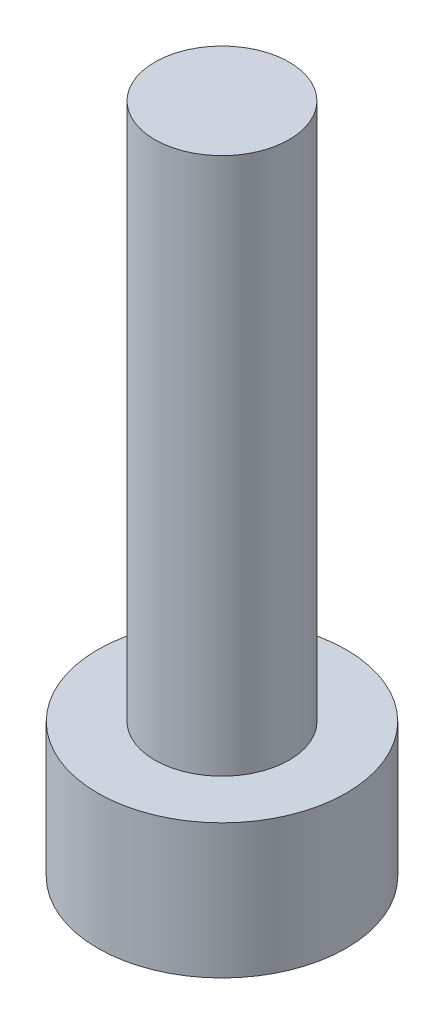
SolidWorks part; units mm, degrees
ref_plane "Front Plane" through (0, 0, 0) normal (0, 0, 1) x (1, 0, 0)
ref_plane "Top Plane" through (0, 0, 0) normal (0, 1, 0) x (1, 0, 0)
ref_plane "Right Plane" through (0, 0, 0) normal (1, 0, 0) x (0, 0, -1)
sketch "Sketch1" plane through (0, 0, 0) normal (0, 1, 0) x (1, 0, 0)
  circle A0 centre (0, 0) radius 1.85
  dimension "D1" = 3.7
extrude "Boss-Extrude1" add sketch "Sketch1" along normal blind 2
sketch "Sketch2" plane through (0, 2, 0) normal (0, 1, 0) x (1, 0, 0)
  circle A0 centre (0, 0) radius 1
  dimension "D1" = 2
extrude "Boss-Extrude2" add sketch "Sketch2" along normal blind 8
